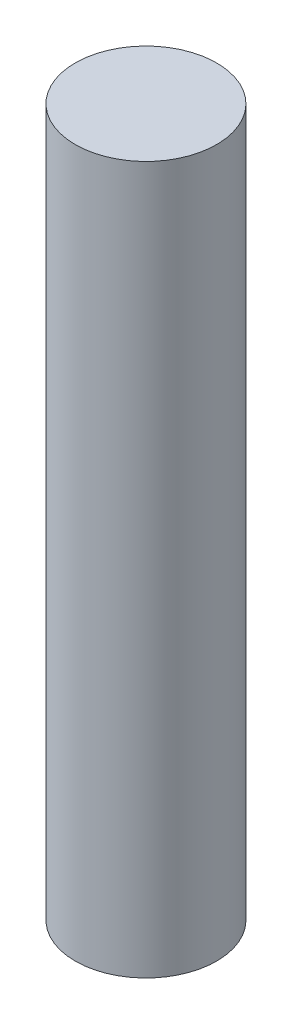
SolidWorks part; units mm, degrees
ref_plane "前视基准面" through (0, 0, 0) normal (0, 0, 1) x (1, 0, 0)
ref_plane "上视基准面" through (0, 0, 0) normal (0, 1, 0) x (1, 0, 0)
ref_plane "右视基准面" through (0, 0, 0) normal (1, 0, 0) x (0, 0, -1)
sketch "草图1" plane through (0, 0, 0) normal (0, 1, 0) x (1, 0, 0)
  circle A0 centre (0, 0) radius 1.5
  dimension "D1" = 3
extrude "拉伸1" add sketch "草图1" along normal blind 15
